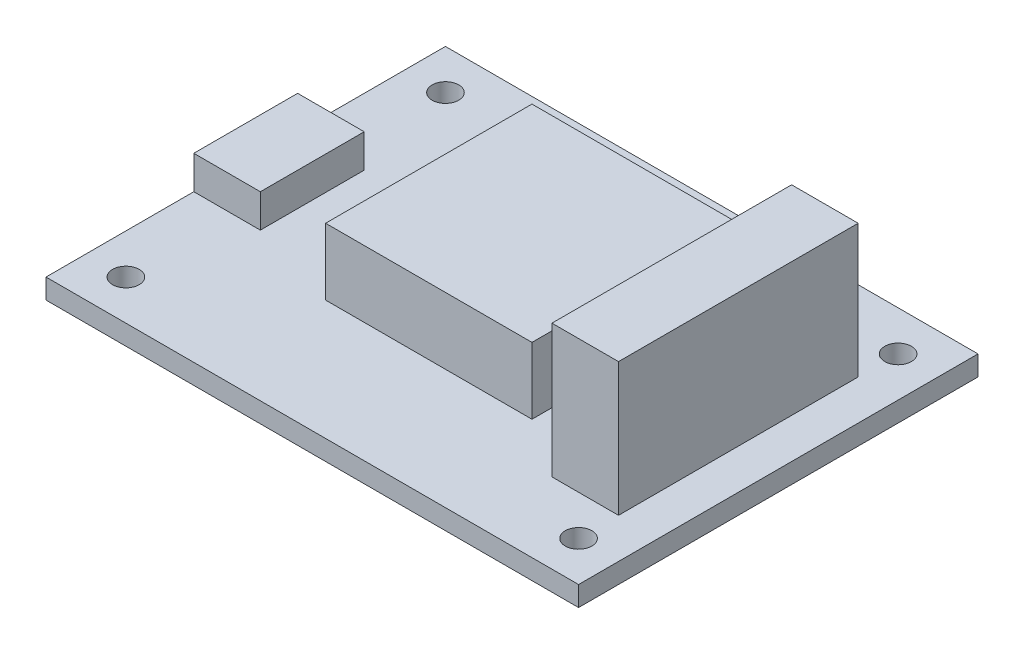
SolidWorks part; units mm, degrees
ref_plane "前视基准面" through (0, 0, 0) normal (0, 0, 1) x (1, 0, 0)
ref_plane "上视基准面" through (0, 0, 0) normal (0, 1, 0) x (1, 0, 0)
ref_plane "右视基准面" through (0, 0, 0) normal (1, 0, 0) x (0, 0, -1)
sketch "草图1" plane through (0, 0, 0) normal (0, 1, 0) x (1, 0, 0)
  line L1 (-20, -15) -> (20, -15)
  line L2 (-20, -15) -> (-20, 15)
  line L3 (-20, 15) -> (20, 15)
  line L4 (20, -15) -> (20, 15)
  line L5 (0, 15) -> (0, -15) construction
  line L6 (-20, 0) -> (20, 0) construction
  circle A0 centre (-17, 12) radius 1
  circle A1 centre (17, 12) radius 1
  circle A2 centre (17, -12) radius 1
  circle A3 centre (-17, -12) radius 1
  point P0 (0, 0)
  dimension "D3" = 2
  dimension "D1" = 40
  dimension "D2" = 30
  dimension "D4" = 34
  dimension "D5" = 24
extrude "凸台-拉伸1" add sketch "草图1" along normal blind 1.5
sketch "草图2" plane through (0, 1.5, 0) normal (0, 1, 0) x (1, 0, 0)
  line L0 (-20, 15) -> (-20, -15) construction
  line L1 (-20, 3.9) -> (-15, 3.9)
  line L2 (-20, 3.9) -> (-20, -3.9)
  line L3 (-20, -3.9) -> (-15, -3.9)
  line L4 (-15, 3.9) -> (-15, -3.9)
  line L5 (-20, 0) -> (-15, 0) construction
  dimension "D1" = 7.8
  dimension "D2" = 5
extrude "凸台-拉伸2" add sketch "草图2" along normal blind 2.5
sketch "草图3" plane through (0, 1.5, 0) normal (0, 1, 0) x (1, 0, 0)
  line L0 (20, 15) -> (-20, 15) construction
  line L1 (-8, 9.5) -> (7.5, 9.5)
  line L2 (-8, 9.5) -> (-8, -6)
  line L3 (-8, -6) -> (7.5, -6)
  line L4 (7.5, 9.5) -> (7.5, -6)
  line L5 (-20, 15) -> (-20, 3.9) construction
  dimension "D1" = 15.5
  dimension "D2" = 5.5
  dimension "D3" = 12
extrude "凸台-拉伸3" add sketch "草图3" along normal blind 5
sketch "草图4" plane through (0, 1.5, 0) normal (0, 1, 0) x (1, 0, 0)
  line L0 (20, -15) -> (20, 15) construction
  line L1 (12, 9) -> (17, 9)
  line L2 (12, 9) -> (12, -9)
  line L3 (12, -9) -> (17, -9)
  line L4 (17, 9) -> (17, -9)
  line L5 (17, 0) -> (12, 0) construction
  dimension "D1" = 5
  dimension "D2" = 18
  dimension "D3" = 3
extrude "凸台-拉伸4" add sketch "草图4" along normal blind 10
